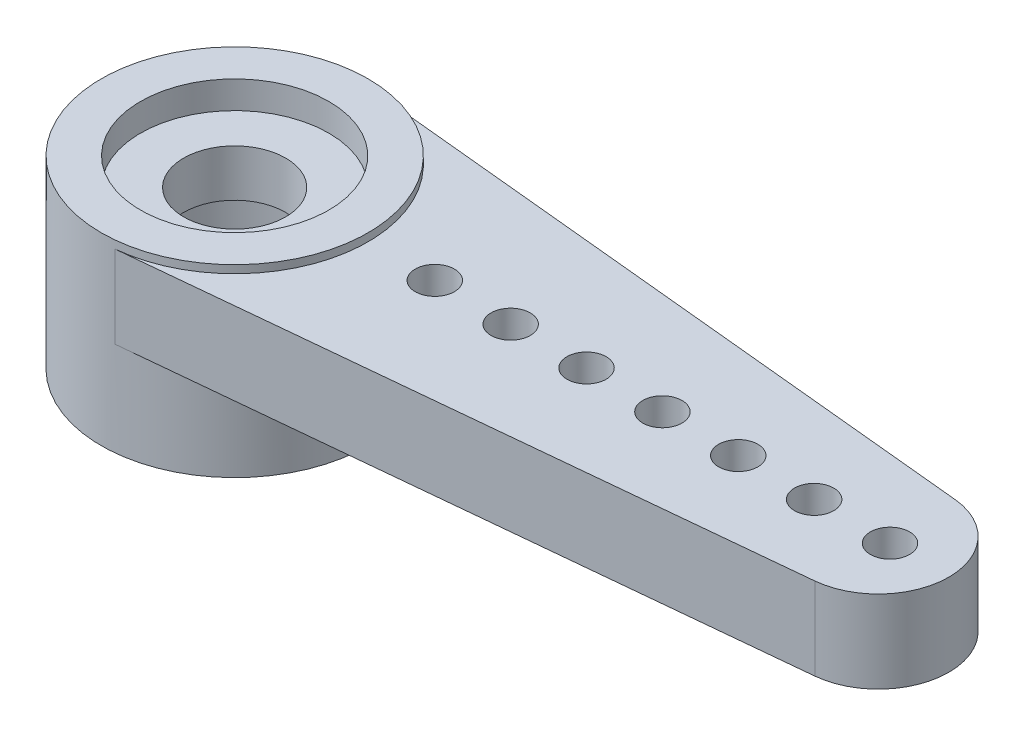
SolidWorks part; units mm, degrees
ref_plane "Front Plane" through (0, 0, 0) normal (0, 0, 1) x (1, 0, 0)
ref_plane "Top Plane" through (0, 0, 0) normal (0, 1, 0) x (1, 0, 0)
ref_plane "Right Plane" through (0, 0, 0) normal (1, 0, 0) x (0, 0, -1)
sketch "Sketch1" plane through (0, 0, 0) normal (0, 0, 1) x (1, 0, 0)
  line L0 (33.4, -2.3) -> (30, -2.3)
  line L1 (30, -2.3) -> (30, -4.7)
  line L2 (30, -4.7) -> (33.4, -4.7)
  line L3 (33.4, -4.7) -> (33.4, -2.3)
  line L4 (30, -2.3) -> (30, -4.7) construction
revolve "Revolve1" add sketch "Sketch1" angle 360 about L4
sketch "Sketch2" plane through (0, -2.3, 0) normal (0, 1, 0) x (-1, 0, 0)
  line L0 (-30.3317, -3.3838) -> (-46.5756, -1.7914)
  line L1 (-46.5756, 1.7914) -> (-30.3317, 3.3838)
  arc A0 (-46.5756, -1.7914) -> (-46.5756, 1.7914) centre (-46.4, 0) cw
  arc A1 (-30.3317, 3.3838) -> (-30.3317, -3.3838) centre (-30, 0) cw
extrude "Boss-Extrude1" add sketch "Sketch2" along normal blind 2.1
sketch "Sketch3" plane through (0, -0.2, 0) normal (0, 1, 0) x (-1, 0, 0)
  circle A0 centre (-30, 0) radius 3.4
extrude "Boss-Extrude2" add sketch "Sketch3" along normal blind 0.2
sketch "Sketch4" plane through (0, 0, 0) normal (0, 0, 1) x (1, 0, 0)
  line L0 (32.4, 0) -> (30, 0)
  line L1 (30, 0) -> (30, -4.7)
  line L2 (30, -4.7) -> (32.4, -4.7)
  line L3 (32.4, -4.7) -> (32.4, -1.9)
  line L4 (32.4, -1.9) -> (31.3, -1.9)
  line L5 (31.3, -1.9) -> (31.3, -0.7)
  line L6 (31.3, -0.7) -> (32.4, -0.7)
  line L7 (32.4, -0.7) -> (32.4, 0)
  line L8 (30, 0) -> (30, -4.7) construction
revolve "Cut-Revolve1" cut sketch "Sketch4" angle 360 about L8
hole_wizard "Ø1.0 (1) Diameter Hole1" positions "Sketch6" profile "Sketch5" hole size "Ø1.0" standard "ANSI Metric"
sketch "Sketch6" plane through (0, -2.3, 0) normal (0, -1, 0) x (-1, 0, 0)
  point P0 (-40.9, 0)
  point P1 (-42.8333, 0)
  point P2 (-37.0333, 0)
  point P3 (-46.7, 0)
  point P4 (-38.9667, 0)
  point P5 (-44.7667, 0)
  point P6 (-35.1, 0)
sketch "Sketch5" plane through (40.9, -2.3, 0) normal (1, 0, 0) x (0, 0, -1)
  line L0 (0, 0) -> (0, 2.3)
  line L1 (0, 2.3) -> (0.5, 2.3)
  line L2 (0.5, 2.3) -> (0.5, 0)
  line L5 (0.5, 0) -> (0, 0)
  line L11 (0, -6.35) -> (0, 107.95) construction
  dimension "Thru Hole Dia." = 1
  dimension "Thru Hole Depth" = 2.3
